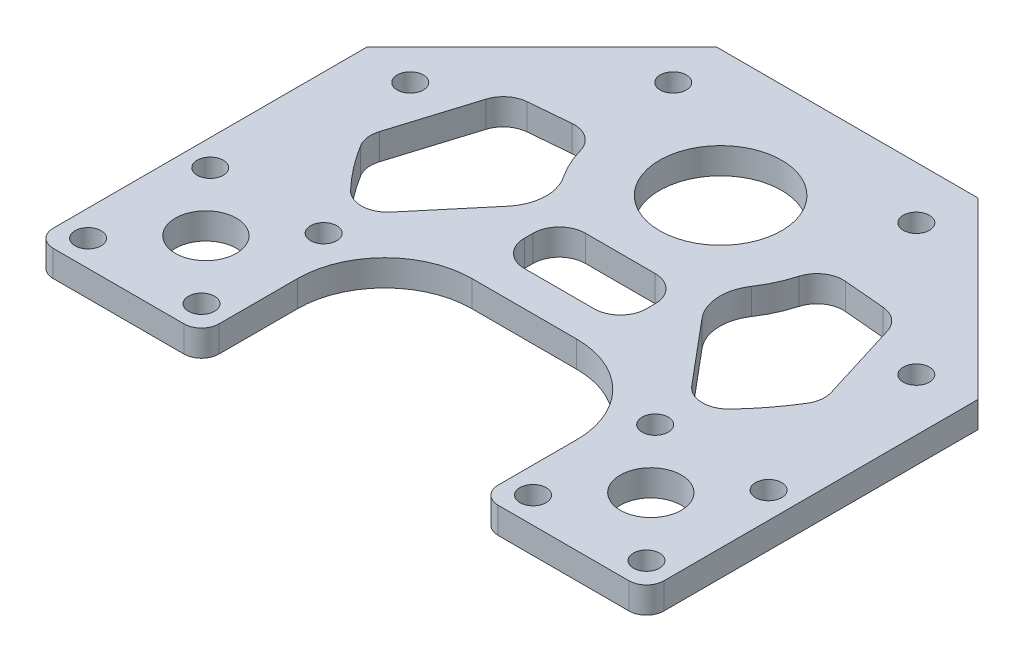
SolidWorks part; units mm, degrees
material "Thornel Mat VMA"
ref_plane "前视基准面" through (0, 0, 0) normal (0, 0, 1) x (1, 0, 0)
ref_plane "上视基准面" through (0, 0, 0) normal (0, 1, 0) x (1, 0, 0)
ref_plane "右视基准面" through (0, 0, 0) normal (1, 0, 0) x (0, 0, -1)
sketch "草图1" plane through (0, 0, 0) normal (0, 1, 0) x (1, 0, 0)
  line L1 (0, 0) -> (70, 0)
  line L2 (0, 0) -> (0, 58)
  line L3 (0, 58) -> (70, 58)
  line L4 (70, 0) -> (70, 58)
  circle A0 centre (35, 43.5) radius 7
  dimension "D3" = 14
  dimension "D1" = 70
  dimension "D2" = 58
  dimension "D4" = 43.5
extrude "凸台-拉伸1" add sketch "草图1" along normal blind 3
chamfer "倒角1" distance 20 angle 45 2 edges at (70, 1.5, -58) (0, 1.5, -58)
sketch "草图2" plane through (0, 3, 0) normal (0, 1, 0) x (1, 0, 0)
  line L0 (0, 0) -> (70, 0) construction
  line L1 (19, 0) -> (51, 0)
  line L2 (19, 0) -> (19, 21)
  line L3 (19, 21) -> (51, 21)
  line L4 (51, 0) -> (51, 21)
  line L5 (19, 0) -> (51, 21) construction
  line L6 (19, 21) -> (51, 0) construction
  line L7 (0, 38) -> (0, 0) construction
  point P0 (35, 10.5)
  dimension "D1" = 10.5
  dimension "D2" = 32
  dimension "D3" = 35
extrude "切除-拉伸1" cut sketch "草图2" against normal blind 3
fillet "圆角1" radius 10 2 edges at (51, 1.5, -21) (19, 1.5, -21)
sketch "草图3" plane through (0, 3, 0) normal (0, 1, 0) x (1, 0, 0)
  line L0 (0, 0) -> (19, 0) construction
  line L1 (3, 3) -> (16, 3) construction
  line L2 (3, 3) -> (3, 17) construction
  line L3 (3, 17) -> (16, 17) construction
  line L4 (16, 3) -> (16, 17) construction
  line L5 (3, 3) -> (16, 17) construction
  line L6 (3, 17) -> (16, 3) construction
  line L7 (0, 38) -> (0, 0) construction
  line L8 (19, 11) -> (19, 0) construction
  line L9 (35, 58) -> (35, 0) construction
  line L10 (50, 58) -> (20, 58) construction
  line L11 (67, 17) -> (54, 3) construction
  line L12 (67, 3) -> (54, 17) construction
  line L13 (54, 3) -> (54, 17) construction
  line L14 (67, 17) -> (54, 17) construction
  line L15 (67, 3) -> (67, 17) construction
  line L16 (67, 3) -> (54, 3) construction
  circle A0 centre (3, 17) radius 1.5
  circle A1 centre (16, 17) radius 1.5
  circle A2 centre (3, 3) radius 1.5
  circle A3 centre (16, 3) radius 1.5
  circle A4 centre (54, 3) radius 1.5
  circle A5 centre (67, 3) radius 1.5
  circle A6 centre (54, 17) radius 1.5
  circle A7 centre (67, 17) radius 1.5
  point P0 (9.5, 10)
  point P30 (60.5, 10)
  dimension "D5" = 3
  dimension "D1" = 10
  dimension "D2" = 3
  dimension "D3" = 9.5
  dimension "D4" = 3
extrude "切除-拉伸2" cut sketch "草图3" against normal through all
sketch "草图4" plane through (0, 0, 0) normal (0, -1, 0) x (1, 0, 0)
  line L0 (50, -58) -> (20, -58) construction
  line L1 (0, -38) -> (20, -58) construction
  line L2 (0, -38) -> (0, 0) construction
  line L3 (35, -21) -> (35, -58) construction
  line L4 (41, -21) -> (29, -21) construction
  circle A0 centre (21.0711, -52) radius 1.5
  circle A1 centre (6, -36.9289) radius 1.5
  circle A2 centre (64, -36.9289) radius 1.5
  circle A3 centre (48.9289, -52) radius 1.5
  dimension "D5" = 3
  dimension "D6" = 3
  dimension "D1" = 6
  dimension "D2" = 5
  dimension "D3" = 5
  dimension "D4" = 6
extrude "切除-拉伸3" cut sketch "草图4" against normal through all
fillet "圆角2" radius 2 4 edges at (0, 1.5, 0) (19, 1.5, 0) (51, 1.5, 0) (70, 1.5, 0)
sketch "草图5" plane through (0, 0, 0) normal (0, -1, 0) x (1, 0, 0)
  line L0 (43.3562, -33.5414) -> (54.2836, -20.5187)
  line L1 (35, -58) -> (35, -2.7336) construction
  line L2 (50, -58) -> (20, -58) construction
  line L3 (47.9505, -42.367) -> (57.4144, -41.539)
  line L4 (57.4144, -41.539) -> (61.279, -29.0288)
  line L5 (26.6438, -33.5414) -> (15.7164, -20.5187)
  line L6 (22.0495, -42.367) -> (12.5856, -41.539)
  line L7 (12.5856, -41.539) -> (8.721, -29.0288)
  line L8 (41, -21) -> (29, -21) construction
  line L9 (28, -32) -> (42, -32)
  line L10 (28, -32) -> (28, -25)
  line L11 (28, -25) -> (42, -25)
  line L12 (42, -32) -> (42, -25)
  line L13 (28, -32) -> (42, -25) construction
  line L14 (28, -25) -> (42, -32) construction
  arc A0 (15.7164, -20.5187) -> (8.721, -29.0288) centre (35, -43.5) ccw
  arc A1 (47.9505, -42.367) -> (43.3562, -33.5414) centre (35, -43.5) ccw
  arc A2 (61.279, -29.0288) -> (54.2836, -20.5187) centre (35, -43.5) ccw
  arc A3 (26.6438, -33.5414) -> (22.0495, -42.367) centre (35, -43.5) ccw
  point P1 (35, -28.5)
  dimension "D1" = 60
  dimension "D2" = 26
  dimension "D3" = 40
  dimension "D4" = 85
  dimension "D5" = 4
  dimension "D6" = 7
  dimension "D7" = 14
extrude "切除-拉伸4" cut sketch "草图5" against normal through all
fillet "圆角3" radius 3 12 edges at (12.5856, 1.5, -41.539) (8.721, 1.5, -29.0288) (15.7164, 1.5, -20.5187) (22.0495, 1.5, -42.367) (57.4144, 1.5, -41.539) (47.9505, 1.5, -42.367) (61.279, 1.5, -29.0288) (54.2836, 1.5, -20.5187) (28, 1.5, -25) (28, 1.5, -32) (42, 1.5, -25) (42, 1.5, -32)
fillet "圆角4" radius 5 2 edges at (26.6438, 1.5, -33.5414) (43.3562, 1.5, -33.5414)
sketch "草图6" plane through (0, 0, 0) normal (0, -1, 0) x (1, 0, 0)
  line L0 (2, 0) -> (17, 0) construction
  line L1 (35, -58) -> (35, 1.943) construction
  line L2 (50, -58) -> (20, -58) construction
  circle A0 centre (9.5, -10) radius 3.5
  circle A1 centre (60.5, -10) radius 3.5
  dimension "D1" = 7
  dimension "D2" = 10
extrude "切除-拉伸5" cut sketch "草图6" against normal blind 10
